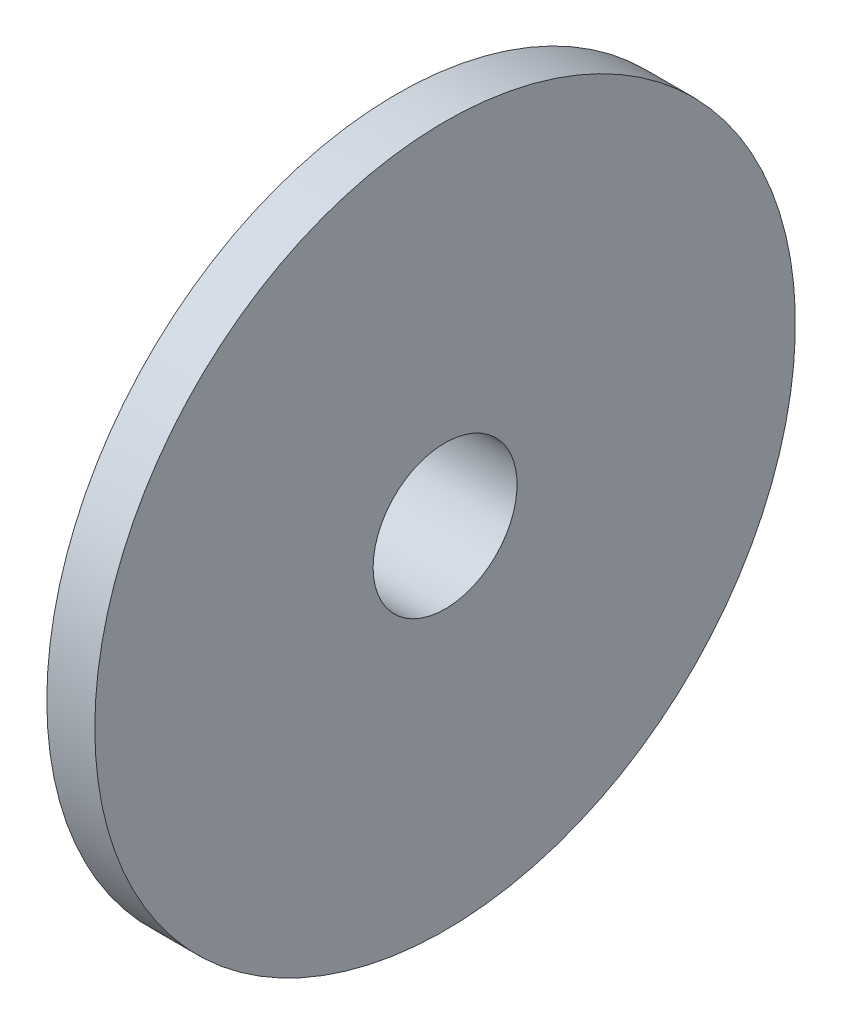
SolidWorks part; units mm, degrees
ref_plane "前视基准面" through (0, 0, 0) normal (0, 0, 1) x (1, 0, 0)
ref_plane "上视基准面" through (0, 0, 0) normal (0, 1, 0) x (1, 0, 0)
ref_plane "右视基准面" through (0, 0, 0) normal (1, 0, 0) x (0, 0, -1)
sketch "草图1" plane through (0, 0, 0) normal (0, 0, 1) x (1, 0, 0)
  line L0 (-9.1, 0) -> (4.0429, 0) construction
  line L1 (0, 9.1) -> (0, -7.5) construction
  line L2 (0, 1.5) -> (0, 7.3)
  line L3 (0, 7.3) -> (-1, 7.3)
  line L4 (-1, 7.3) -> (-1, 2.75)
  line L5 (-1, 2.75) -> (-3, 2.75)
  line L6 (-3, 2.75) -> (-3, 1.5)
  line L7 (-3, 1.5) -> (0, 1.5)
  dimension "D1" = 3
  dimension "D2" = 5.5
  dimension "D3" = 1
  dimension "D4" = 3
  dimension "D5" = 14.6
revolve "旋转1" add sketch "草图1" angle 360 about L0
chamfer "倒角1" distance 0.2 angle 45 2 edges at (-3, 0, 2.75) (-3, 0, 1.5)
